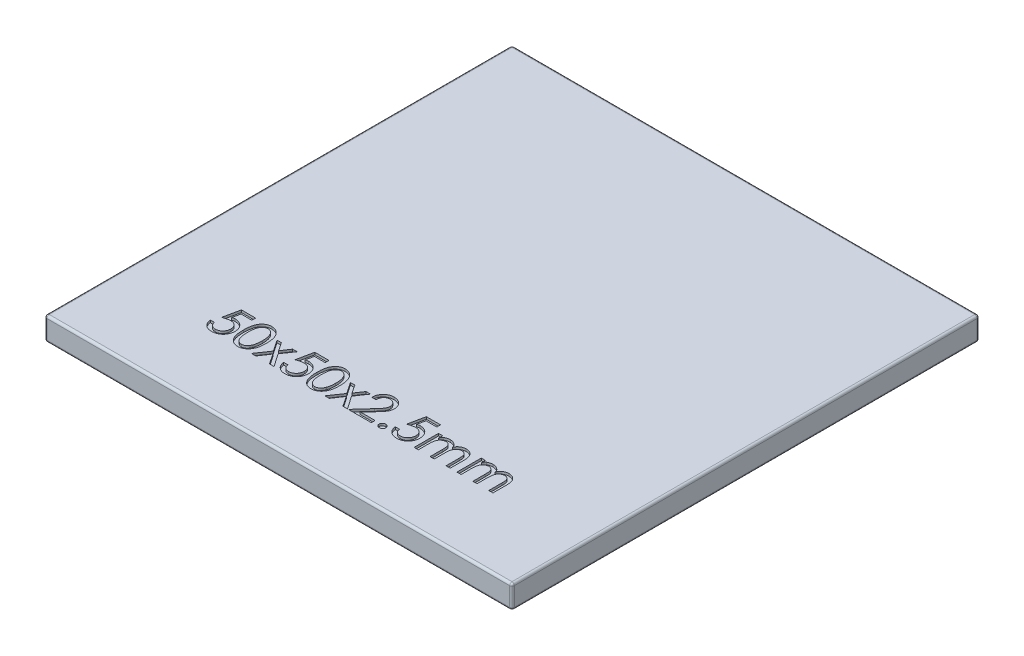
SolidWorks part; units mm, degrees
ref_plane "Plan de face" through (0, 0, 0) normal (0, 0, 1) x (1, 0, 0)
ref_plane "Plan de dessus" through (0, 0, 0) normal (0, 1, 0) x (1, 0, 0)
ref_plane "Plan de droite" through (0, 0, 0) normal (1, 0, 0) x (0, 0, -1)
sketch "Esquisse1" plane through (0, 0, 0) normal (0, 1, 0) x (1, 0, 0)
  line L1 (-25, -25) -> (25, -25)
  line L2 (-25, -25) -> (-25, 25)
  line L3 (-25, 25) -> (25, 25)
  line L4 (25, -25) -> (25, 25)
  line L5 (-25, -25) -> (25, 25) construction
  line L6 (-25, 25) -> (25, -25) construction
  point P0 (0, 0)
  dimension "D1" = 50
  dimension "D2" = 50
extrude "Boss.-Extru.1" add sketch "Esquisse1" along normal blind 2.5
sketch "Esquisse2" plane through (0, 2.5, 0) normal (0, 1, 0) x (1, 0, 0)
  text T0 "<b>50x50x2.5mm</b>"
extrude "Enlèv. mat.-Extru.1" cut sketch "Esquisse2" against normal blind 0.25
fillet "Congé1" radius 0.25 12 edges at (-25, 1.25, -25) (-25, 1.25, 25) (25, 1.25, -25) (25, 1.25, 25) (-25, 2.5, 0) (-25, 0, 0) (0, 2.5, -25) (0, 0, -25) (25, 2.5, 0) (25, 0, 0) (0, 2.5, 25) (0, 0, 25)
